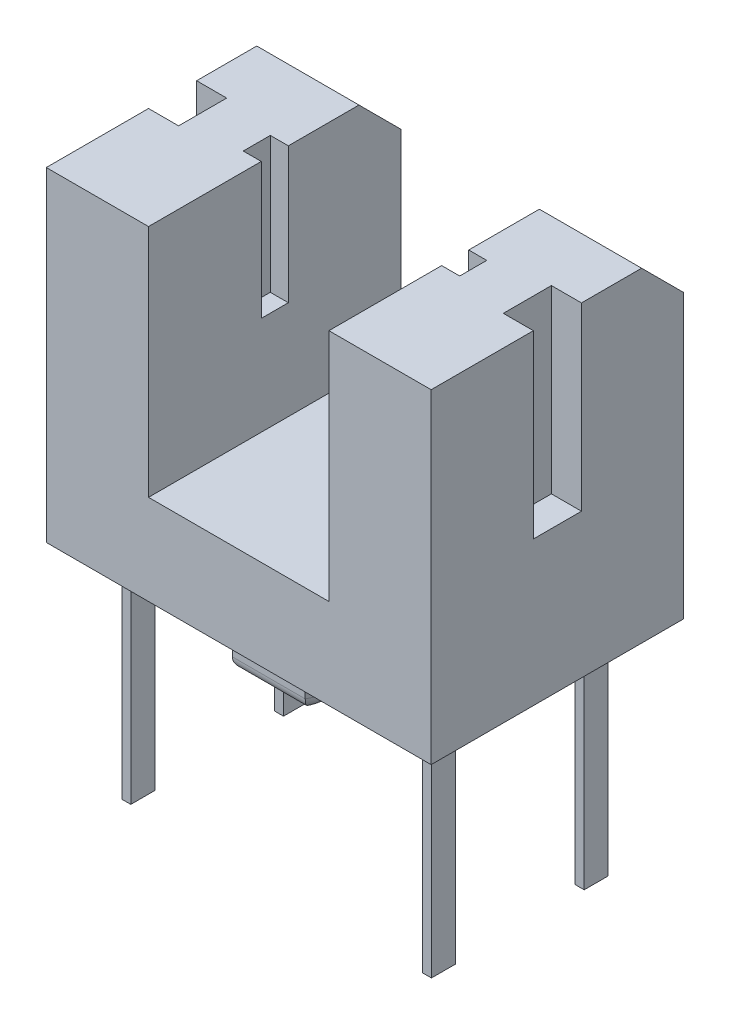
SolidWorks part; units mm, degrees
ref_plane "Front Plane" through (0, 0, 0) normal (0, 0, 1) x (1, 0, 0)
ref_plane "Top Plane" through (0, 0, 0) normal (0, 1, 0) x (1, 0, 0)
ref_plane "Right Plane" through (0, 0, 0) normal (1, 0, 0) x (0, 0, -1)
sketch "Sketch2" plane through (0, 0, 0) normal (0, 1, 0) x (1, 0, 0)
  line L1 (-3.2, -2.1) -> (3.2, -2.1)
  line L2 (-3.2, -2.1) -> (-3.2, 2.1)
  line L3 (-3.2, 2.1) -> (3.2, 2.1)
  line L4 (3.2, -2.1) -> (3.2, 2.1)
  line L5 (-3.2, -2.1) -> (3.2, 2.1) construction
  line L6 (-3.2, 2.1) -> (3.2, -2.1) construction
  point P0 (0, 0)
  dimension "D1" = 4.2
  dimension "D2" = 6.4
extrude "Boss-Extrude1" add sketch "Sketch2" along normal blind 1.5
sketch "Sketch3" plane through (0, 1.5, 0) normal (0, 1, 0) x (1, 0, 0)
  line L0 (0, 2.1) -> (0, -2.1) construction
  line L1 (3.2, 2.1) -> (-3.2, 2.1) construction
  line L2 (-3.2, -2.1) -> (3.2, -2.1) construction
  line L3 (-3.2, 2.1) -> (-3.2, -2.1)
  line L4 (3.2, 2.1) -> (1.5, 2.1)
  line L5 (3.2, 2.1) -> (3.2, -2.1)
  line L6 (3.2, -2.1) -> (1.5, -2.1)
  line L7 (1.5, 2.1) -> (1.5, -2.1)
  line L8 (-3.2, 2.1) -> (-1.5, 2.1)
  line L9 (-1.5, 2.1) -> (-1.5, -2.1)
  line L10 (-3.2, -2.1) -> (-1.5, -2.1)
  dimension "D1" = 3
extrude "Boss-Extrude2" add sketch "Sketch3" along normal blind 3.9
sketch "Sketch4" plane through (0, 0, 0) normal (0, -1, 0) x (1, 0, 0)
  line L0 (0, 2.1) -> (0, -2.1) construction
  line L1 (-3.2, 2.1) -> (3.2, 2.1) construction
  line L2 (3.2, -2.1) -> (-3.2, -2.1) construction
  line L3 (-3.2, 0) -> (3.2, 0) construction
  line L4 (-3.2, -2.1) -> (-3.2, 2.1) construction
  line L5 (3.2, 2.1) -> (3.2, -2.1) construction
  line L6 (2.5, 1.27) -> (2.5, -1.27) construction
  line L7 (-2.5, 1.27) -> (-2.5, -1.27) construction
  line L8 (2.575, 1.47) -> (2.575, 1.07)
  line L9 (-2.575, 1.47) -> (-2.425, 1.47)
  line L10 (-2.575, 1.47) -> (-2.575, 1.07)
  line L11 (-2.575, 1.07) -> (-2.425, 1.07)
  line L12 (-2.425, 1.47) -> (-2.425, 1.07)
  line L13 (-2.575, 1.47) -> (-2.425, 1.07) construction
  line L14 (-2.575, 1.07) -> (-2.425, 1.47) construction
  line L15 (2.575, 1.47) -> (2.425, 1.07) construction
  line L16 (2.575, 1.07) -> (2.425, 1.47) construction
  line L17 (2.575, 1.47) -> (2.425, 1.47)
  line L18 (2.425, 1.47) -> (2.425, 1.07)
  line L19 (2.575, 1.07) -> (2.425, 1.07)
  line L20 (2.575, -1.47) -> (2.575, -1.07)
  line L21 (-2.575, -1.47) -> (-2.425, -1.47)
  line L22 (-2.575, -1.47) -> (-2.575, -1.07)
  line L23 (-2.575, -1.07) -> (-2.425, -1.07)
  line L24 (-2.425, -1.47) -> (-2.425, -1.07)
  line L25 (-2.575, -1.47) -> (-2.425, -1.07) construction
  line L26 (-2.575, -1.07) -> (-2.425, -1.47) construction
  line L27 (2.575, -1.47) -> (2.425, -1.07) construction
  line L28 (2.575, -1.07) -> (2.425, -1.47) construction
  line L29 (2.575, -1.47) -> (2.425, -1.47)
  line L30 (2.425, -1.47) -> (2.425, -1.07)
  line L31 (2.575, -1.07) -> (2.425, -1.07)
  point P19 (2.5, 0)
  point P29 (2.5, 1.27)
  point P34 (2.5, -1.27)
  dimension "D1" = 5
  dimension "D2" = 2.54
  dimension "D3" = 0.4
  dimension "D4" = 0.15
  dimension "D5" = 0.4
extrude "Boss-Extrude3" add sketch "Sketch4" along normal blind 3.7
sketch "Sketch5" plane through (0, 0, 0) normal (0, -1, 0) x (1, 0, 0)
  line L0 (-3.2, 0) -> (3.2, 0) construction
  line L1 (-3.2, -2.1) -> (-3.2, 2.1) construction
  line L2 (3.2, 2.1) -> (3.2, -2.1) construction
  line L3 (0, 1.25) -> (0, -1.25) construction
  line L4 (-3.2, 1.6) -> (-3.2, -1.6) construction
  line L5 (-3.2, 1.6) -> (3.2, 1.6) construction
  line L6 (-3.2, -1.6) -> (3.2, -1.6) construction
  line L7 (-0.6062, 1.6) -> (0.6062, 1.6)
  line L8 (-0.3571, -1.6) -> (0.3571, -1.6)
  circle A0 centre (0, 1.25) radius 0.7 construction
  circle A1 centre (0, -1.25) radius 0.5 construction
  arc A2 (-0.3571, -1.6) -> (0.3571, -1.6) centre (0, -1.25) cw
  arc A3 (-0.6062, 1.6) -> (0.6062, 1.6) centre (0, 1.25) ccw
  point P9 (0, 0)
  point P14 (-3.2, 0)
  dimension "D2" = 1
  dimension "D3" = 1.4
  dimension "D1" = 2.5
  dimension "D4" = 3.2
extrude "Boss-Extrude4" add sketch "Sketch5" along normal blind 0.8
fillet "Fillet1" radius 0.2 2 edges at (0, -0.8, 1.6) (0, -0.8, 0.55)
fillet "Fillet2" radius 0.1 2 edges at (0, -0.8, -1.6) (0, -0.8, -0.75)
sketch "Sketch6" plane through (-1.5, 0, 0) normal (1, 0, 0) x (0, 0, -1)
  line L0 (0, 5.4) -> (0, 0) construction
  line L1 (-2.1, 5.4) -> (2.1, 5.4) construction
  line L2 (-0.225, 5.4) -> (0.225, 5.4) construction
  line L4 (-0.225, 5.4) -> (0.225, 5.4)
  line L5 (-0.225, 5.4) -> (-0.225, 3.14)
  line L6 (-0.225, 3.14) -> (0.225, 3.14)
  line L7 (0.225, 5.4) -> (0.225, 3.14)
  point P8 (0, 5.4)
  dimension "D1" = 0.45
  dimension "D2" = 2.26
extrude "Cut-Extrude1" cut sketch "Sketch6" against normal blind 0.3
sketch "Sketch7" plane through (-3.2, 0, 0) normal (-1, 0, 0) x (0, 0, 1)
  line L0 (0, 5.4) -> (0, 0) construction
  line L1 (-2.1, 5.4) -> (2.1, 5.4) construction
  line L2 (-0.4, 5.4) -> (0.4, 5.4) construction
  line L4 (-0.4, 5.4) -> (0.4, 5.4)
  line L5 (-0.4, 5.4) -> (-0.4, 2.4)
  line L6 (-0.4, 2.4) -> (0.4, 2.4)
  line L7 (0.4, 5.4) -> (0.4, 2.4)
  point P5 (0, 2.4)
  point P8 (0, 5.4)
  dimension "D1" = 0.8
  dimension "D2" = 3
extrude "Cut-Extrude2" cut sketch "Sketch7" against normal blind 0.5
chamfer "Chamfer3" distance 0.7 angle 45 2 edges at (2.35, 5.4, -2.1) (-2.35, 5.4, -2.1)
mirror "Mirror5" about plane through (0, 0, 0) normal (1, 0, 0) of "Cut-Extrude1", "Cut-Extrude2"
equation "\"2ю54\"=2.55944"
